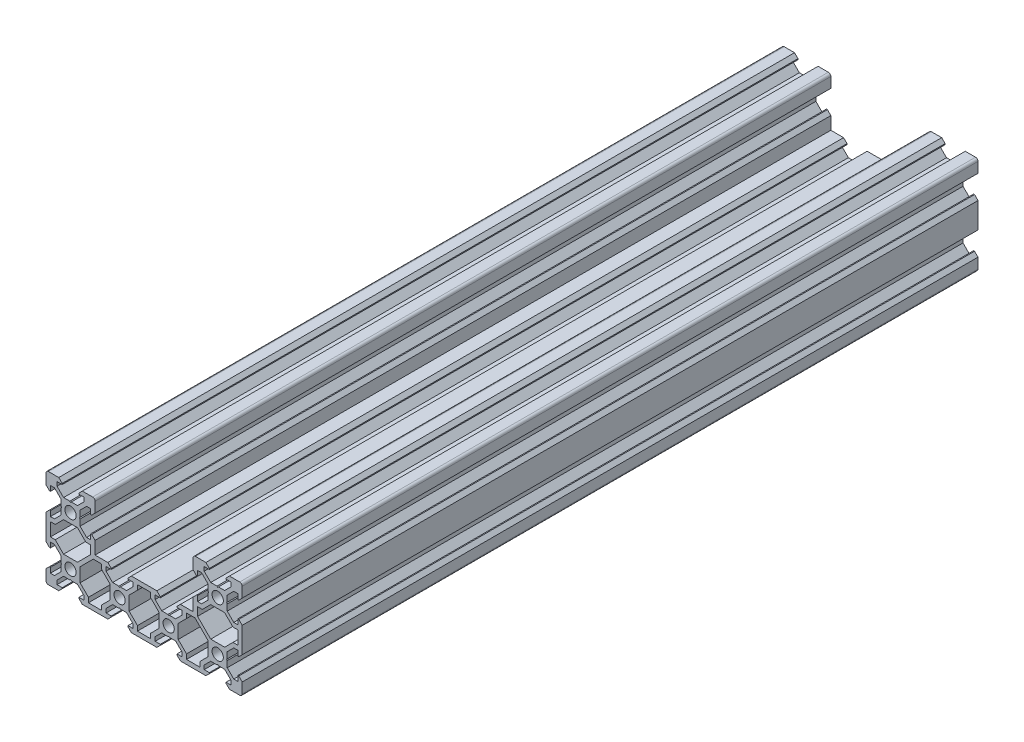
SolidWorks part; units mm, degrees
material "6063-T5"
ref_plane "Front" through (0, 0, 0) normal (0, 0, 1) x (1, 0, 0)
ref_plane "Top" through (0, 0, 0) normal (0, 1, 0) x (1, 0, 0)
ref_plane "Right" through (0, 0, 0) normal (1, 0, 0) x (0, 0, -1)
sketch "Esboço1" plane through (0, 0, 0) normal (1, 0, 0) x (0, 0, -1)
  line L0 (0, 0) -> (-300, 0)
  dimension "D1" = 300
other "C-beam PF20-15 - PERFIL 4080 C-BEAM(1)"
ref_plane "Plano1" through (0, 0, 0) normal (0, 0, 1) x (0, -1, 0)
sketch "Esboço2" plane through (0, 0, 0) normal (0, 0, 1) x (0, -1, 0)
  line L0 (-2.7, -36.2393) -> (-2.7, -38.2)
  line L1 (-6.1, -32.8393) -> (-2.7, -36.2393)
  line L2 (-6.1, -27.1607) -> (-6.1, -32.8393)
  line L3 (-2.7, -23.7607) -> (-6.1, -27.1607)
  line L4 (-2.7, -21.8) -> (-2.7, -23.7607)
  line L5 (0.7393, -21.8) -> (-2.7, -21.8)
  line L6 (6.1, -27.1607) -> (0.7393, -21.8)
  line L7 (6.1, -32.8393) -> (6.1, -27.1607)
  line L8 (2.7, -36.2393) -> (6.1, -32.8393)
  line L9 (2.7, -38.2) -> (2.7, -36.2393)
  line L10 (-2.7, -38.2) -> (2.7, -38.2)
  line L11 (16.2393, -22.7) -> (18.2, -22.7)
  line L12 (12.8393, -26.1) -> (16.2393, -22.7)
  line L13 (7.1607, -26.1) -> (12.8393, -26.1)
  line L14 (1.8, -20.7393) -> (7.1607, -26.1)
  line L15 (1.8, -17.3) -> (1.8, -20.7393)
  line L16 (3.7607, -17.3) -> (1.8, -17.3)
  line L17 (7.1607, -13.9) -> (3.7607, -17.3)
  line L18 (12.8393, -13.9) -> (7.1607, -13.9)
  line L19 (16.2393, -17.3) -> (12.8393, -13.9)
  line L20 (18.2, -17.3) -> (16.2393, -17.3)
  line L21 (18.2, -22.7) -> (18.2, -17.3)
  line L22 (16.2393, -2.7) -> (18.2, -2.7)
  line L23 (12.8393, -6.1) -> (16.2393, -2.7)
  line L24 (7.1607, -6.1) -> (12.8393, -6.1)
  line L25 (3.7607, -2.7) -> (7.1607, -6.1)
  line L26 (1.8, -2.7) -> (3.7607, -2.7)
  line L27 (1.8, 2.7) -> (1.8, -2.7)
  line L28 (3.7607, 2.7) -> (1.8, 2.7)
  line L29 (7.1607, 6.1) -> (3.7607, 2.7)
  line L30 (12.8393, 6.1) -> (7.1607, 6.1)
  line L31 (16.2393, 2.7) -> (12.8393, 6.1)
  line L32 (18.2, 2.7) -> (16.2393, 2.7)
  line L33 (18.2, -2.7) -> (18.2, 2.7)
  line L34 (2.7, 38.2) -> (-2.7, 38.2)
  line L35 (2.7, 36.2393) -> (2.7, 38.2)
  line L36 (6.1, 32.8393) -> (2.7, 36.2393)
  line L37 (6.1, 27.1607) -> (6.1, 32.8393)
  line L38 (0.7393, 21.8) -> (6.1, 27.1607)
  line L39 (-2.7, 21.8) -> (0.7393, 21.8)
  line L40 (-2.7, 23.7607) -> (-2.7, 21.8)
  line L41 (-6.1, 27.1607) -> (-2.7, 23.7607)
  line L42 (-6.1, 32.8393) -> (-6.1, 27.1607)
  line L43 (-2.7, 36.2393) -> (-6.1, 32.8393)
  line L44 (-2.7, 38.2) -> (-2.7, 36.2393)
  line L45 (18.2, 17.3) -> (18.2, 22.7)
  line L46 (16.2393, 17.3) -> (18.2, 17.3)
  line L47 (12.8393, 13.9) -> (16.2393, 17.3)
  line L48 (7.1607, 13.9) -> (12.8393, 13.9)
  line L49 (3.7607, 17.3) -> (7.1607, 13.9)
  line L50 (1.8, 17.3) -> (3.7607, 17.3)
  line L51 (1.8, 20.7393) -> (1.8, 17.3)
  line L52 (7.1607, 26.1) -> (1.8, 20.7393)
  line L53 (12.8393, 26.1) -> (7.1607, 26.1)
  line L54 (16.2393, 22.7) -> (12.8393, 26.1)
  line L55 (18.2, 22.7) -> (16.2393, 22.7)
  line L56 (-15.5, 23.4393) -> (-12.8393, 26.1)
  line L57 (-12.8393, 26.1) -> (-10.3, 26.1)
  line L58 (-10.3, 26.1) -> (-10, 26.4)
  line L59 (-10, 26.4) -> (-9.7, 26.1)
  line L60 (-9.7, 26.1) -> (-7.1607, 26.1)
  line L61 (-7.1607, 26.1) -> (-4.5, 23.4393)
  line L62 (-4.5, 23.4393) -> (-4.5, 21.8)
  line L63 (-4.5, 21.8) -> (-6.6, 21.8)
  line L65 (-6.6, 21.4) -> (-5.2, 20)
  line L66 (-5.2, 20) -> (0, 20)
  line L67 (0, 20) -> (0, 14.8)
  line L68 (0, 14.8) -> (1.4, 13.4)
  line L70 (1.8, 13.4) -> (1.8, 15.5)
  line L71 (1.8, 15.5) -> (3.4393, 15.5)
  line L72 (3.4393, 15.5) -> (6.1, 12.8393)
  line L73 (6.1, 12.8393) -> (6.1, 10.3)
  line L74 (6.1, 10.3) -> (6.4, 10)
  line L75 (6.4, 10) -> (6.1, 9.7)
  line L76 (6.1, 9.7) -> (6.1, 7.1607)
  line L77 (6.1, 7.1607) -> (3.4393, 4.5)
  line L78 (3.4393, 4.5) -> (1.8, 4.5)
  line L79 (1.8, 4.5) -> (1.8, 6.6)
  line L81 (1.4, 6.6) -> (0, 5.2)
  line L82 (0, 5.2) -> (0, -5.2)
  line L83 (0, -5.2) -> (1.4, -6.6)
  line L85 (1.8, -6.6) -> (1.8, -4.5)
  line L86 (1.8, -4.5) -> (3.4393, -4.5)
  line L87 (3.4393, -4.5) -> (6.1, -7.1607)
  line L88 (6.1, -7.1607) -> (6.1, -9.7)
  line L89 (6.1, -9.7) -> (6.4, -10)
  line L90 (6.4, -10) -> (6.1, -10.3)
  line L91 (6.1, -10.3) -> (6.1, -12.8393)
  line L92 (6.1, -12.8393) -> (3.4393, -15.5)
  line L93 (3.4393, -15.5) -> (1.8, -15.5)
  line L94 (1.8, -15.5) -> (1.8, -13.4)
  line L96 (1.4, -13.4) -> (0, -14.8)
  line L97 (0, -14.8) -> (0, -20)
  line L98 (0, -20) -> (-5.2, -20)
  line L99 (-5.2, -20) -> (-6.6, -21.4)
  line L101 (-6.6, -21.8) -> (-4.5, -21.8)
  line L102 (-4.5, -21.8) -> (-4.5, -23.4393)
  line L103 (-4.5, -23.4393) -> (-7.1607, -26.1)
  line L104 (-7.1607, -26.1) -> (-9.7, -26.1)
  line L105 (-9.7, -26.1) -> (-10, -26.4)
  line L106 (-10, -26.4) -> (-10.3, -26.1)
  line L107 (-10.3, -26.1) -> (-12.8393, -26.1)
  line L108 (-12.8393, -26.1) -> (-15.5, -23.4393)
  line L109 (-15.5, -23.4393) -> (-15.5, -21.8)
  line L110 (-15.5, -21.8) -> (-13.4, -21.8)
  line L112 (-13.4, -21.4) -> (-14.8, -20)
  line L113 (-14.8, -20) -> (-19, -20)
  line L114 (-20, -21) -> (-20, -25.2)
  line L115 (-20, -25.2) -> (-18.6, -26.6)
  line L117 (-18.2, -26.6) -> (-18.2, -24.5)
  line L118 (-18.2, -24.5) -> (-16.5607, -24.5)
  line L119 (-16.5607, -24.5) -> (-13.9, -27.1607)
  line L120 (-13.9, -27.1607) -> (-13.9, -29.7)
  line L121 (-13.9, -29.7) -> (-13.6, -30)
  line L122 (-13.6, -30) -> (-13.9, -30.3)
  line L123 (-13.9, -30.3) -> (-13.9, -32.8393)
  line L124 (-13.9, -32.8393) -> (-16.5607, -35.5)
  line L125 (-16.5607, -35.5) -> (-18.2, -35.5)
  line L126 (-18.2, -35.5) -> (-18.2, -33.4)
  line L128 (-18.6, -33.4) -> (-20, -34.8)
  line L129 (-20, -34.8) -> (-20, -39)
  line L130 (-19, -40) -> (-14.8, -40)
  line L131 (-14.8, -40) -> (-13.4, -38.6)
  line L133 (-13.4, -38.2) -> (-15.5, -38.2)
  line L134 (-15.5, -38.2) -> (-15.5, -36.5607)
  line L135 (-15.5, -36.5607) -> (-12.8393, -33.9)
  line L136 (-12.8393, -33.9) -> (-10.3, -33.9)
  line L137 (-10.3, -33.9) -> (-10, -33.6)
  line L138 (-10, -33.6) -> (-9.7, -33.9)
  line L139 (-9.7, -33.9) -> (-7.1607, -33.9)
  line L140 (-7.1607, -33.9) -> (-4.5, -36.5607)
  line L141 (-4.5, -36.5607) -> (-4.5, -38.2)
  line L142 (-4.5, -38.2) -> (-6.6, -38.2)
  line L144 (-6.6, -38.6) -> (-5.2, -40)
  line L145 (-5.2, -40) -> (5.2, -40)
  line L146 (5.2, -40) -> (6.6, -38.6)
  line L148 (6.6, -38.2) -> (4.5, -38.2)
  line L149 (4.5, -38.2) -> (4.5, -36.5607)
  line L150 (4.5, -36.5607) -> (7.1607, -33.9)
  line L151 (7.1607, -33.9) -> (9.7, -33.9)
  line L152 (9.7, -33.9) -> (10, -33.6)
  line L153 (10, -33.6) -> (10.3, -33.9)
  line L154 (10.3, -33.9) -> (12.8393, -33.9)
  line L155 (12.8393, -33.9) -> (15.5, -36.5607)
  line L156 (15.5, -36.5607) -> (15.5, -38.2)
  line L157 (15.5, -38.2) -> (13.4, -38.2)
  line L159 (13.4, -38.6) -> (14.8, -40)
  line L160 (14.8, -40) -> (19, -40)
  line L161 (20, -39) -> (20, -34.8)
  line L162 (20, -34.8) -> (18.6, -33.4)
  line L164 (18.2, -33.4) -> (18.2, -35.5)
  line L165 (18.2, -35.5) -> (16.5607, -35.5)
  line L166 (16.5607, -35.5) -> (13.9, -32.8393)
  line L167 (13.9, -32.8393) -> (13.9, -30.3)
  line L168 (13.9, -30.3) -> (13.6, -30)
  line L169 (13.6, -30) -> (13.9, -29.7)
  line L170 (13.9, -29.7) -> (13.9, -27.1607)
  line L171 (13.9, -27.1607) -> (16.5607, -24.5)
  line L172 (16.5607, -24.5) -> (18.2, -24.5)
  line L173 (18.2, -24.5) -> (18.2, -26.6)
  line L175 (18.6, -26.6) -> (20, -25.2)
  line L176 (20, -25.2) -> (20, -14.8)
  line L177 (20, -14.8) -> (18.6, -13.4)
  line L179 (18.2, -13.4) -> (18.2, -15.5)
  line L180 (18.2, -15.5) -> (16.5607, -15.5)
  line L181 (16.5607, -15.5) -> (13.9, -12.8393)
  line L182 (13.9, -12.8393) -> (13.9, -10.3)
  line L183 (13.9, -10.3) -> (13.6, -10)
  line L184 (13.6, -10) -> (13.9, -9.7)
  line L185 (13.9, -9.7) -> (13.9, -7.1607)
  line L186 (13.9, -7.1607) -> (16.5607, -4.5)
  line L187 (16.5607, -4.5) -> (18.2, -4.5)
  line L188 (18.2, -4.5) -> (18.2, -6.6)
  line L190 (18.6, -6.6) -> (20, -5.2)
  line L191 (20, -5.2) -> (20, 5.2)
  line L192 (20, 5.2) -> (18.6, 6.6)
  line L194 (18.2, 6.6) -> (18.2, 4.5)
  line L195 (18.2, 4.5) -> (16.5607, 4.5)
  line L196 (16.5607, 4.5) -> (13.9, 7.1607)
  line L197 (13.9, 7.1607) -> (13.9, 9.7)
  line L198 (13.9, 9.7) -> (13.6, 10)
  line L199 (13.6, 10) -> (13.9, 10.3)
  line L200 (13.9, 10.3) -> (13.9, 12.8393)
  line L201 (13.9, 12.8393) -> (16.5607, 15.5)
  line L202 (16.5607, 15.5) -> (18.2, 15.5)
  line L203 (18.2, 15.5) -> (18.2, 13.4)
  line L205 (18.6, 13.4) -> (20, 14.8)
  line L206 (20, 14.8) -> (20, 25.2)
  line L207 (20, 25.2) -> (18.6, 26.6)
  line L209 (18.2, 26.6) -> (18.2, 24.5)
  line L210 (18.2, 24.5) -> (16.5607, 24.5)
  line L211 (16.5607, 24.5) -> (13.9, 27.1607)
  line L212 (13.9, 27.1607) -> (13.9, 29.7)
  line L213 (13.9, 29.7) -> (13.6, 30)
  line L214 (13.6, 30) -> (13.9, 30.3)
  line L215 (13.9, 30.3) -> (13.9, 32.8393)
  line L216 (13.9, 32.8393) -> (16.5607, 35.5)
  line L217 (16.5607, 35.5) -> (18.2, 35.5)
  line L218 (18.2, 35.5) -> (18.2, 33.4)
  line L220 (18.6, 33.4) -> (20, 34.8)
  line L221 (20, 34.8) -> (20, 39)
  line L222 (19, 40) -> (14.8, 40)
  line L223 (14.8, 40) -> (13.4, 38.6)
  line L225 (13.4, 38.2) -> (15.5, 38.2)
  line L226 (15.5, 38.2) -> (15.5, 36.5607)
  line L227 (15.5, 36.5607) -> (12.8393, 33.9)
  line L228 (12.8393, 33.9) -> (10.3, 33.9)
  line L229 (10.3, 33.9) -> (10, 33.6)
  line L230 (10, 33.6) -> (9.7, 33.9)
  line L231 (9.7, 33.9) -> (7.1607, 33.9)
  line L232 (7.1607, 33.9) -> (4.5, 36.5607)
  line L233 (4.5, 36.5607) -> (4.5, 38.2)
  line L234 (4.5, 38.2) -> (6.6, 38.2)
  line L236 (6.6, 38.6) -> (5.2, 40)
  line L237 (5.2, 40) -> (-5.2, 40)
  line L238 (-5.2, 40) -> (-6.6, 38.6)
  line L240 (-6.6, 38.2) -> (-4.5, 38.2)
  line L241 (-4.5, 38.2) -> (-4.5, 36.5607)
  line L242 (-4.5, 36.5607) -> (-7.1607, 33.9)
  line L243 (-7.1607, 33.9) -> (-9.7, 33.9)
  line L244 (-9.7, 33.9) -> (-10, 33.6)
  line L245 (-10, 33.6) -> (-10.3, 33.9)
  line L246 (-10.3, 33.9) -> (-12.8393, 33.9)
  line L247 (-12.8393, 33.9) -> (-15.5, 36.5607)
  line L248 (-15.5, 36.5607) -> (-15.5, 38.2)
  line L249 (-15.5, 38.2) -> (-13.4, 38.2)
  line L251 (-13.4, 38.6) -> (-14.8, 40)
  line L252 (-14.8, 40) -> (-19, 40)
  line L253 (-20, 39) -> (-20, 34.8)
  line L254 (-20, 34.8) -> (-18.6, 33.4)
  line L256 (-18.2, 33.4) -> (-18.2, 35.5)
  line L257 (-18.2, 35.5) -> (-16.5607, 35.5)
  line L258 (-16.5607, 35.5) -> (-13.9, 32.8393)
  line L259 (-13.9, 32.8393) -> (-13.9, 30.3)
  line L260 (-13.9, 30.3) -> (-13.6, 30)
  line L261 (-13.6, 30) -> (-13.9, 29.7)
  line L262 (-13.9, 29.7) -> (-13.9, 27.1607)
  line L263 (-13.9, 27.1607) -> (-16.5607, 24.5)
  line L264 (-16.5607, 24.5) -> (-18.2, 24.5)
  line L265 (-18.2, 24.5) -> (-18.2, 26.6)
  line L267 (-18.6, 26.6) -> (-20, 25.2)
  line L268 (-20, 25.2) -> (-20, 21)
  line L269 (-19, 20) -> (-14.8, 20)
  line L270 (-14.8, 20) -> (-13.4, 21.4)
  line L272 (-13.4, 21.8) -> (-15.5, 21.8)
  line L273 (-15.5, 21.8) -> (-15.5, 23.4393)
  line L280 (-18.6, 26.6) -> (-18.2, 26.6)
  line L281 (-13.4, 38.6) -> (-13.4, 38.2)
  line L282 (6.6, 38.6) -> (6.6, 38.2)
  line L283 (1.4, 6.6) -> (1.8, 6.6)
  line L284 (1.4, -13.4) -> (1.8, -13.4)
  line L285 (-18.6, -33.4) -> (-18.2, -33.4)
  line L286 (-18.6, 33.4) -> (-18.2, 33.4)
  line L287 (-6.6, 38.6) -> (-6.6, 38.2)
  line L288 (13.4, 38.6) -> (13.4, 38.2)
  line L289 (1.4, 13.4) -> (1.8, 13.4)
  line L290 (1.4, -6.6) -> (1.8, -6.6)
  line L291 (-18.6, -26.6) -> (-18.2, -26.6)
  line L300 (-13.4, 21.8) -> (-13.4, 21.4)
  line L301 (-13.4, -21.4) -> (-13.4, -21.8)
  line L302 (-6.6, 21.8) -> (-6.6, 21.4)
  line L303 (-6.6, -21.4) -> (-6.6, -21.8)
  line L318 (-13.4, -38.2) -> (-13.4, -38.6)
  line L319 (-6.6, -38.2) -> (-6.6, -38.6)
  line L320 (6.6, -38.2) -> (6.6, -38.6)
  line L322 (13.4, -38.2) -> (13.4, -38.6)
  line L324 (18.2, -33.4) -> (18.6, -33.4)
  line L325 (18.2, -26.6) -> (18.6, -26.6)
  line L326 (18.2, -13.4) -> (18.6, -13.4)
  line L327 (18.2, -6.6) -> (18.6, -6.6)
  line L328 (18.2, 6.6) -> (18.6, 6.6)
  line L329 (18.2, 13.4) -> (18.6, 13.4)
  line L330 (18.2, 26.6) -> (18.6, 26.6)
  line L331 (18.2, 33.4) -> (18.6, 33.4)
  circle A0 centre (10, -30) radius 2.3
  circle A1 centre (-10, -30) radius 2.3
  arc A2 (-19, -20) -> (-20, -21) centre (-19, -21) ccw
  arc A3 (-20, -39) -> (-19, -40) centre (-19, -39) ccw
  arc A4 (19, -40) -> (20, -39) centre (19, -39) ccw
  arc A5 (20, 39) -> (19, 40) centre (19, 39) ccw
  arc A6 (-19, 40) -> (-20, 39) centre (-19, 39) ccw
  arc A7 (-20, 21) -> (-19, 20) centre (-19, 21) ccw
  circle A8 centre (10, -10) radius 2.3
  circle A9 centre (10, 10) radius 2.3
  circle A10 centre (-10, 30) radius 2.3
  circle A11 centre (10, 30) radius 2.3
  point P45 (0, 0)
  point P298 (0, 10)
  point P299 (-10, 20)
  point P300 (-20, 20)
  point P301 (-20, 30)
  point P302 (-20, 40)
  point P303 (-10, 40)
  point P304 (10, 40)
  point P305 (20, 40)
  point P306 (20, 30)
  point P307 (20, 10)
  point P308 (20, -10)
  point P309 (20, -30)
  point P310 (20, -40)
  point P311 (10, -40)
  point P312 (-10, -40)
  point P313 (-20, -40)
  point P314 (-20, -30)
  point P315 (-20, -20)
  point P316 (-10, -20)
  point P317 (0, -10)
  point P319 (-10, -30)
  point P320 (10, -30)
  point P321 (10, -10)
  point P322 (10, 10)
  point P323 (10, 30)
  point P324 (-10, 30)
